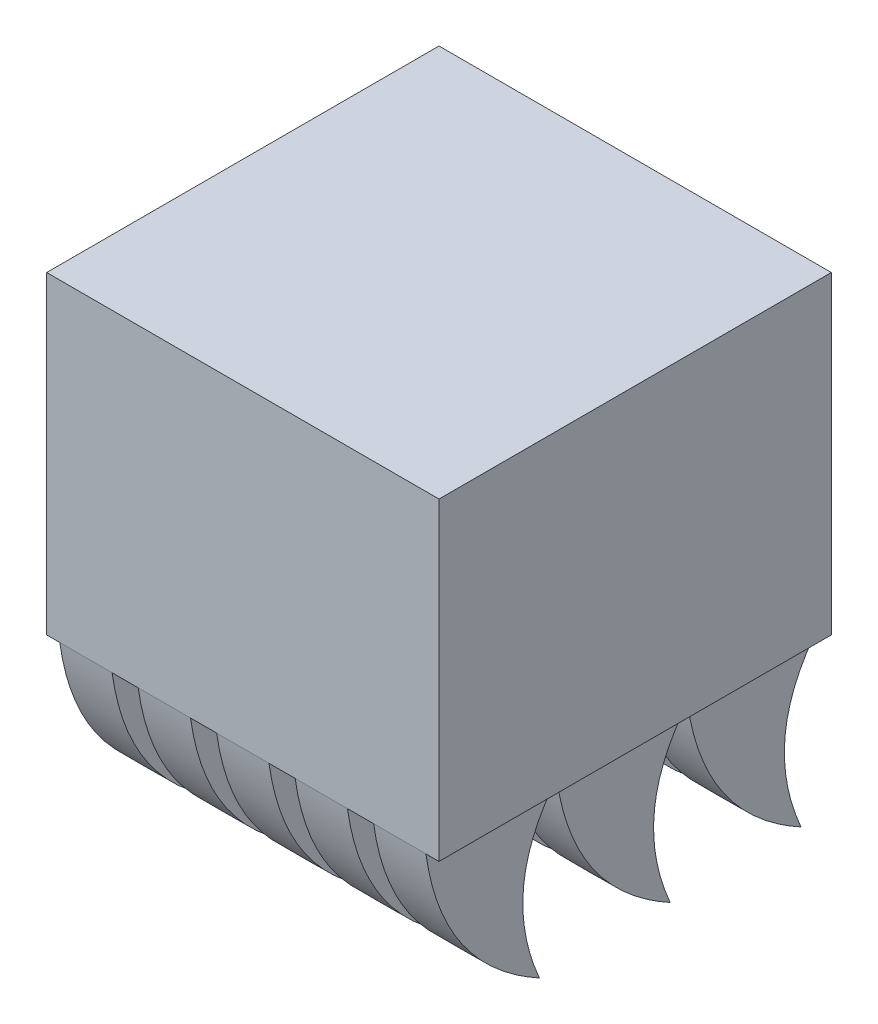
SolidWorks part; units mm, degrees
ref_plane "정면" through (0, 0, 0) normal (0, 0, 1) x (1, 0, 0)
ref_plane "윗면" through (0, 0, 0) normal (0, 1, 0) x (1, 0, 0)
ref_plane "우측면" through (0, 0, 0) normal (1, 0, 0) x (0, 0, -1)
sketch "스케치1" plane through (0, 0, 0) normal (0, 1, 0) x (1, 0, 0)
  line L1 (-7.5, -7.5) -> (7.5, -7.5)
  line L2 (-7.5, -7.5) -> (-7.5, 7.5)
  line L3 (-7.5, 7.5) -> (7.5, 7.5)
  line L4 (7.5, -7.5) -> (7.5, 7.5)
  line L5 (-7.5, -7.5) -> (7.5, 7.5) construction
  line L6 (-7.5, 7.5) -> (7.5, -7.5) construction
  point P0 (0, 0)
  dimension "D1" = 15
  dimension "D2" = 15
extrude "보스-돌출1" add sketch "스케치1" along normal mid plane 12
sketch "스케치3" plane through (0, 0, 0) normal (1, 0, 0) x (0, 0, -1)
  line L4 (2.5, -6) -> (7.5, -6)
  spline S0 degree 2 poles (2.5, -6) (3.0981, -10.2259) (6.8379, -12.2781) knots 0 0 0 1 1 1
  spline S1 degree 2 poles (6.8379, -12.2781) (5.2994, -8.7305) (7.5, -6) knots 0 0 0 1 1 1
  dimension "D1" = 5
extrude "보스-돌출2" add sketch "스케치3" along normal mid plane 2
sketch "스케치5" plane through (0, -6, 0) normal (0, -1, 0) x (1, 0, 0)
  line L0 (1, -7.5) -> (1, -2.5) construction
  line L1 (1, -2.5) -> (-1, -2.5) construction
  line L2 (-7.5, 7.5) -> (7.5, 7.5) construction
  line L3 (-7.5, -7.5) -> (-7.5, 7.5) construction
  line L4 (7.5, 7.5) -> (7.5, -7.5) construction
  point P0 (0, -5)
  point P3 (1, -5)
  point P6 (0, -2.5)
  point P7 (-5, 4.84)
  point P8 (5, 4.84)
  dimension "D1" = 2.66
  dimension "D2" = 2.5
  dimension "D3" = 2.5
  dimension "D4" = 2.66
pattern_sketch "스케치 패턴2" [suppressed]
pattern_linear "선형 패턴1" count 3 spacing 3 along (-1, 0, 0) count 3 spacing 5 along (0, 0, 1) of "보스-돌출2"
pattern_linear "선형 패턴2" count 3 spacing 3 along (-1, 0, 0) count 3 spacing 5 along (0, 0, -1) of "보스-돌출2"
